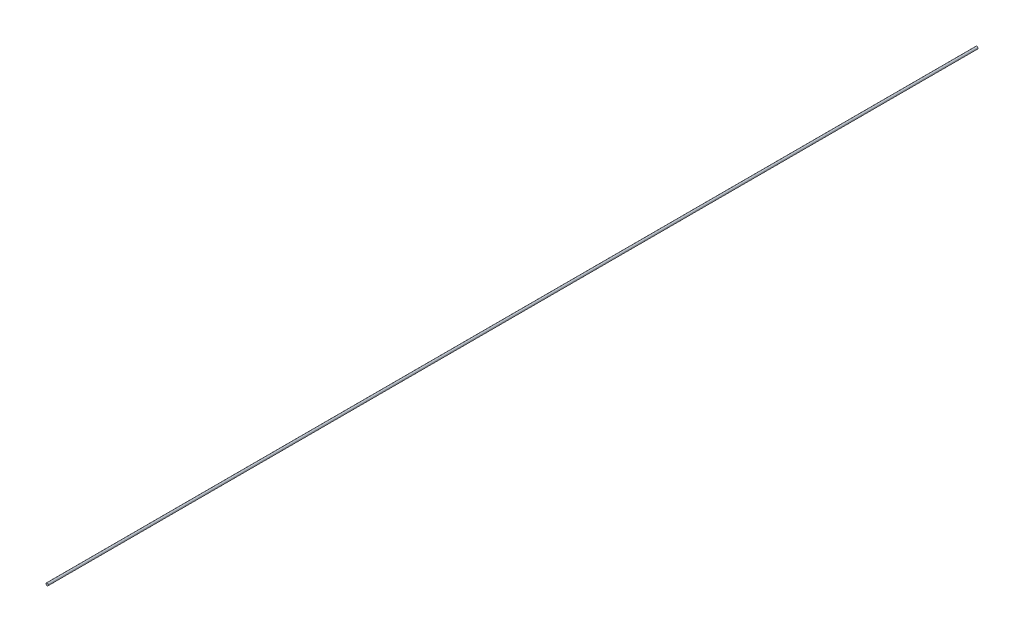
SolidWorks part; units mm, degrees
material "ABS PC"
ref_plane "Plan de face" through (0, 0, 0) normal (0, 0, 1) x (1, 0, 0)
ref_plane "Plan de dessus" through (0, 0, 0) normal (0, 1, 0) x (1, 0, 0)
ref_plane "Plan de droite" through (0, 0, 0) normal (1, 0, 0) x (0, 0, -1)
sketch "Esquisse1" plane through (0, 0, 0) normal (0, 0, 1) x (1, 0, 0)
  circle A0 centre (0, 0) radius 1
  dimension "D1" = 2
extrude "Boss.-Extru.1" add sketch "Esquisse1" along normal blind 800
